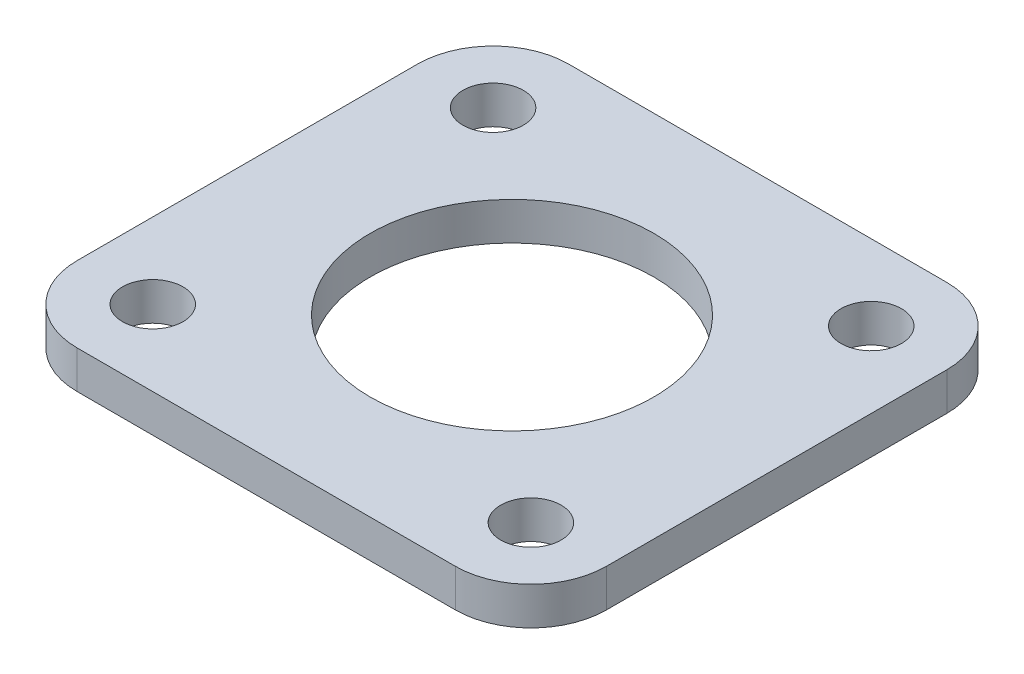
SolidWorks part; units mm, degrees
material "Thornel Mat VMA"
ref_plane "前视基准面" through (0, 0, 0) normal (0, 0, 1) x (1, 0, 0)
ref_plane "上视基准面" through (0, 0, 0) normal (0, 1, 0) x (1, 0, 0)
ref_plane "右视基准面" through (0, 0, 0) normal (1, 0, 0) x (0, 0, -1)
other "Configuration Table"
sketch "草图1" plane through (0, 0, 0) normal (0, 1, 0) x (1, 0, 0)
  line L1 (-10, 9) -> (10, 9) construction
  line L2 (-10, 9) -> (-10, -9) construction
  line L3 (-10, -9) -> (10, -9) construction
  line L4 (10, 9) -> (10, -9) construction
  line L5 (-10, 9) -> (10, -9) construction
  line L6 (-10, -9) -> (10, 9) construction
  line L7 (-14, 13) -> (14, 13)
  line L8 (-14, 13) -> (-14, -13)
  line L9 (-14, -13) -> (14, -13)
  line L10 (14, 13) -> (14, -13)
  line L11 (-14, 13) -> (14, -13) construction
  line L12 (-14, -13) -> (14, 13) construction
  circle A0 centre (10, -9) radius 1.6
  circle A1 centre (-10, -9) radius 1.6
  circle A2 centre (-10, 9) radius 1.6
  circle A3 centre (10, 9) radius 1.6
  point P0 (0, 0)
  point P10 (0, 0)
  dimension "D3" = 3.2
  dimension "D1" = 20
  dimension "D2" = 18
  dimension "D4" = 4
  dimension "D5" = 4
extrude "凸台-拉伸1" add sketch "草图1" along normal blind 2
sketch "草图2" plane through (0, 2, 0) normal (0, 1, 0) x (1, 0, 0)
  circle A0 centre (0, 0) radius 7.5
  dimension "D1" = 15
extrude "切除-拉伸1" cut sketch "草图2" against normal blind 2
fillet "圆角1" radius 4 4 edges at (-14, 1, 13) (-14, 1, -13) (14, 1, -13) (14, 1, 13)
